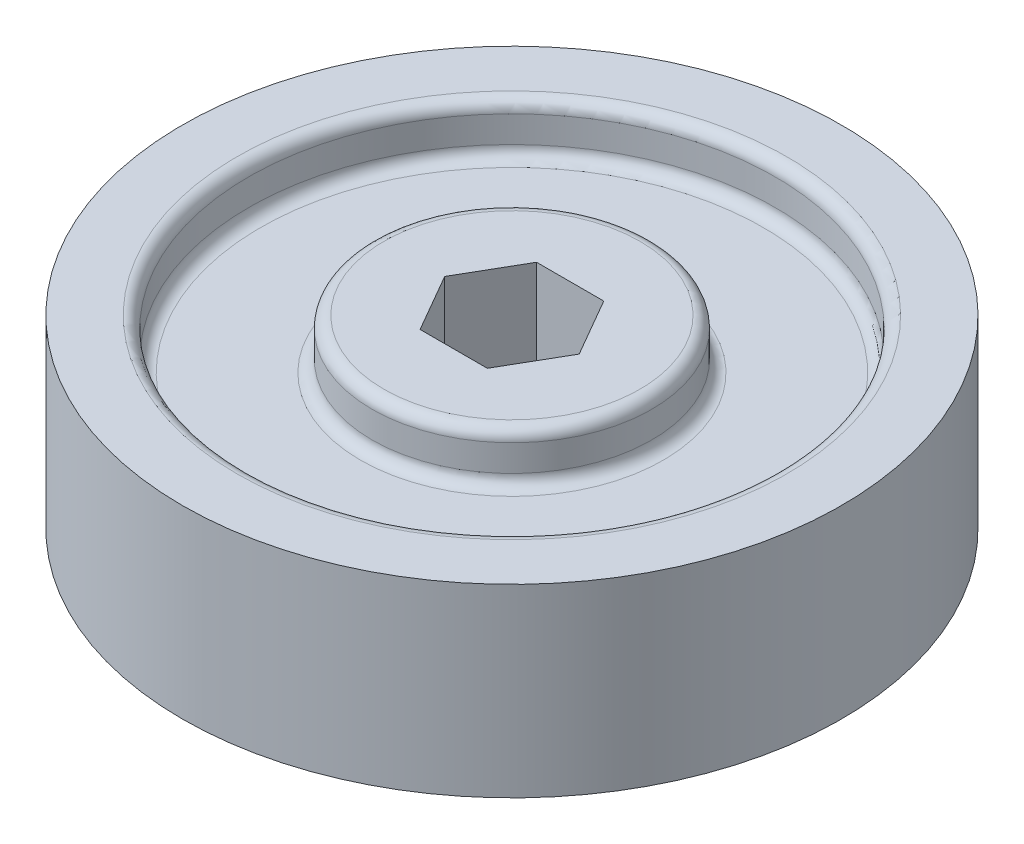
SolidWorks part; units mm, degrees
ref_plane "Front Plane" through (0, 0, 0) normal (0, 0, 1) x (1, 0, 0)
ref_plane "Top Plane" through (0, 0, 0) normal (0, 1, 0) x (1, 0, 0)
ref_plane "Right Plane" through (0, 0, 0) normal (1, 0, 0) x (0, 0, -1)
sketch "Sketch1" plane through (0, 0, 0) normal (0, 1, 0) x (1, 0, 0)
  line L1 (3.6662, -6.35) -> (7.3323, 0)
  line L2 (7.3323, 0) -> (3.6662, 6.35)
  line L3 (3.6662, 6.35) -> (-3.6662, 6.35)
  line L4 (-3.6662, 6.35) -> (-7.3323, 0)
  line L5 (-7.3323, 0) -> (-3.6662, -6.35)
  line L6 (-3.6662, -6.35) -> (3.6662, -6.35)
  circle A0 centre (0, 0) radius 35.941
  circle A1 centre (0, 0) radius 6.35 construction
  dimension "D1" = 71.882
  dimension "D2" = 12.7
extrude "Boss-Extrude1" add sketch "Sketch1" along normal blind 20.1676
sketch "Sketch2" plane through (0, 20.1676, 0) normal (0, 1, 0) x (1, 0, 0)
  circle A0 centre (0, 0) radius 15.24
  circle A1 centre (0, 0) radius 28.702
  dimension "D1" = 57.404
  dimension "D2" = 30.48
extrude "Cut-Extrude1" cut sketch "Sketch2" against normal blind 5.4356
sketch "Sketch3" plane through (0, 0, 0) normal (0, -1, 0) x (1, 0, 0)
  circle A0 centre (0, 0) radius 15.24
  circle A1 centre (0, 0) radius 28.702
  dimension "D1" = 57.404
  dimension "D2" = 30.48
extrude "Cut-Extrude2" cut sketch "Sketch3" against normal blind 5.4356
fillet "Fillet2" radius 1.27 8 edges at (0, 14.732, 28.702) (0, 20.1676, 15.24) (0, 14.732, 15.24) (0, 20.1676, 28.702) (0, 0, -28.702) (0, 5.4356, -28.702) (0, 5.4356, -15.24) (0, 0, -15.24)
